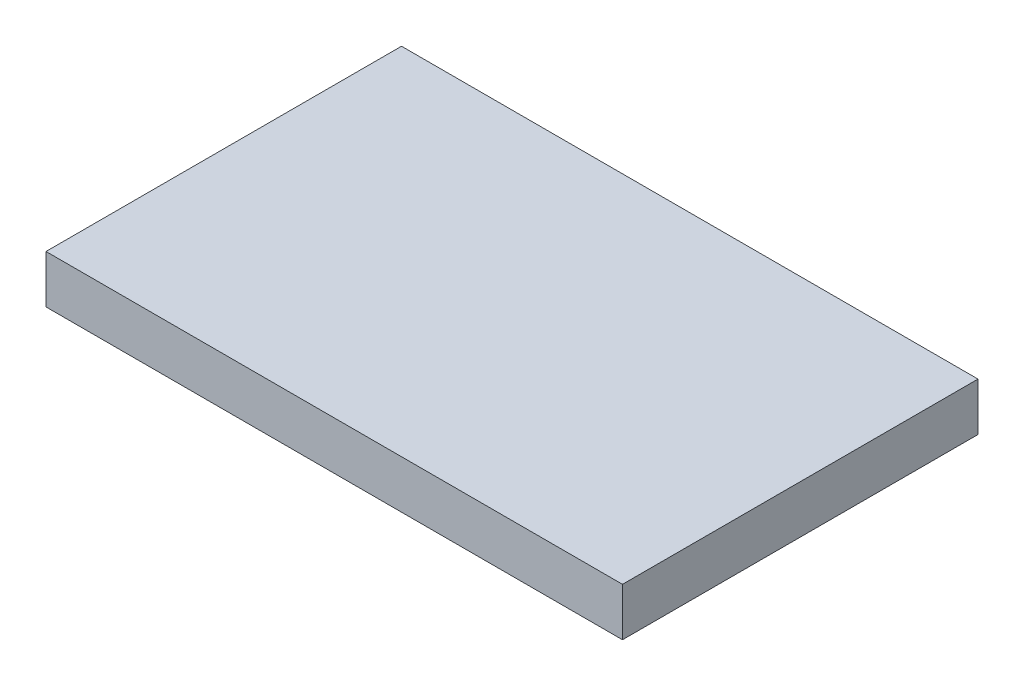
SolidWorks part; units mm, degrees
ref_plane "Plan de face" through (0, 0, 0) normal (0, 0, 1) x (1, 0, 0)
ref_plane "Plan de dessus" through (0, 0, 0) normal (0, 1, 0) x (1, 0, 0)
ref_plane "Plan de droite" through (0, 0, 0) normal (1, 0, 0) x (0, 0, -1)
sketch "Esquisse1" plane through (0, 0, 0) normal (0, 1, 0) x (1, 0, 0)
  line L1 (-30, 18.5) -> (30, 18.5)
  line L2 (-30, 18.5) -> (-30, -18.5)
  line L3 (-30, -18.5) -> (30, -18.5)
  line L4 (30, 18.5) -> (30, -18.5)
  line L5 (-30, 18.5) -> (30, -18.5) construction
  line L6 (-30, -18.5) -> (30, 18.5) construction
  point P0 (0, 0)
  dimension "D1" = 60
  dimension "D2" = 37
extrude "Boss.-Extru.1" add sketch "Esquisse1" along normal blind 5
ref_plane "Plan1" through (30, 5, 18.5) normal (0, 0, -1) x (-1, 0, 0)
